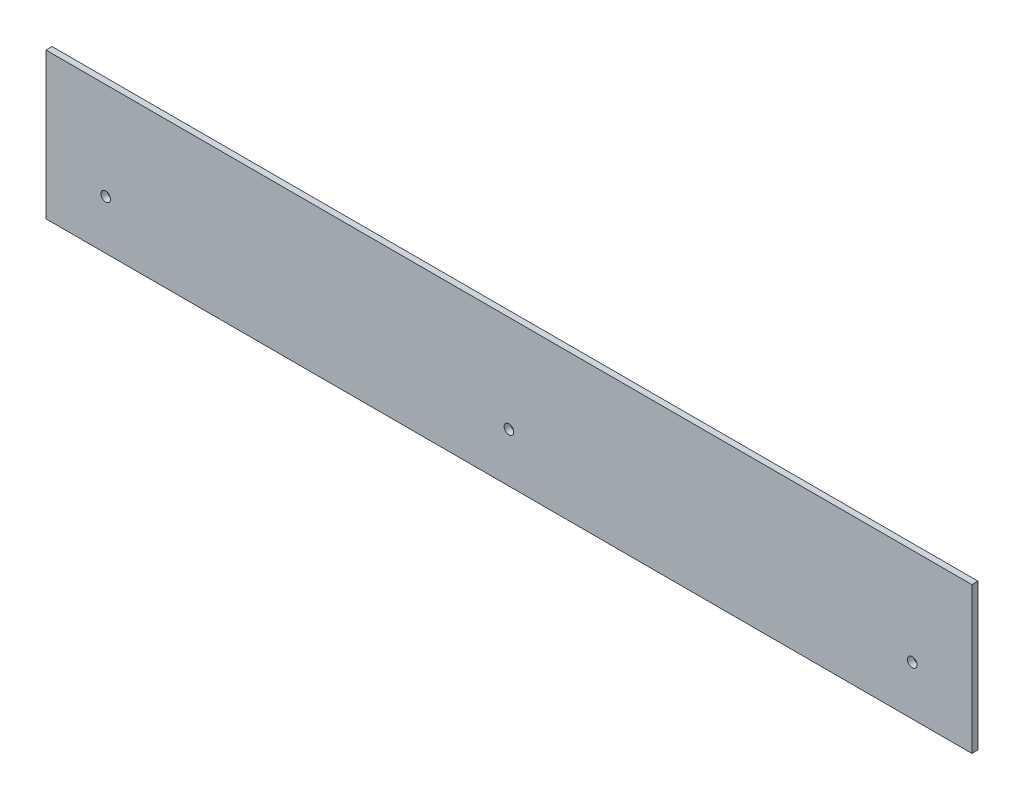
SolidWorks part; units mm, degrees
ref_plane "Front" through (0, 0, 0) normal (0, 0, 1) x (1, 0, 0)
ref_plane "Top" through (0, 0, 0) normal (0, 1, 0) x (1, 0, 0)
ref_plane "Right" through (0, 0, 0) normal (1, 0, 0) x (0, 0, -1)
sketch "Sketch1" plane through (0, 0, 0) normal (0, 0, 1) x (1, 0, 0)
  line L1 (-241.3, 38.1) -> (241.3, 38.1)
  line L2 (-241.3, 38.1) -> (-241.3, -38.1)
  line L3 (-241.3, -38.1) -> (241.3, -38.1)
  line L4 (241.3, 38.1) -> (241.3, -38.1)
  line L5 (-241.3, 38.1) -> (241.3, -38.1) construction
  line L6 (-241.3, -38.1) -> (241.3, 38.1) construction
  point P0 (0, 0)
  dimension "D1" = 482.6
  dimension "D2" = 76.2
extrude "Boss-Extrude1" add sketch "Sketch1" along normal blind 3.175 contours L1 L4 L3 L2
sketch "Sketch2" plane through (0, 0, 3.175) normal (0, 0, 1) x (1, 0, 0)
  line L0 (0, -1.7463) -> (0, 1.7463) construction
  line L4 (-241.3, 38.1) -> (-241.3, -38.1)
  line L5 (-241.3, -38.1) -> (241.3, -38.1)
  line L6 (241.3, -38.1) -> (241.3, 38.1)
  line L7 (241.3, 38.1) -> (-241.3, 38.1)
  line L8 (-241.3, 38.1) -> (-241.3, -38.1)
  line L9 (-241.3, -38.1) -> (241.3, -38.1)
  line L10 (241.3, -38.1) -> (241.3, 38.1)
  line L11 (241.3, 38.1) -> (-241.3, 38.1)
  circle A0 centre (-210.185, -12.446) radius 2.5
  circle A1 centre (210.185, -12.446) radius 2.5
  circle A2 centre (0, -12.446) radius 2.5
  dimension "D2" = 5
  dimension "D5" = 25.654
  dimension "D3" = 25.654
  dimension "D4" = 31.115
  dimension "D1" = 0
extrude "Cut-Extrude1" cut sketch "Sketch2" against normal through all contours A0 | A1 | A2
